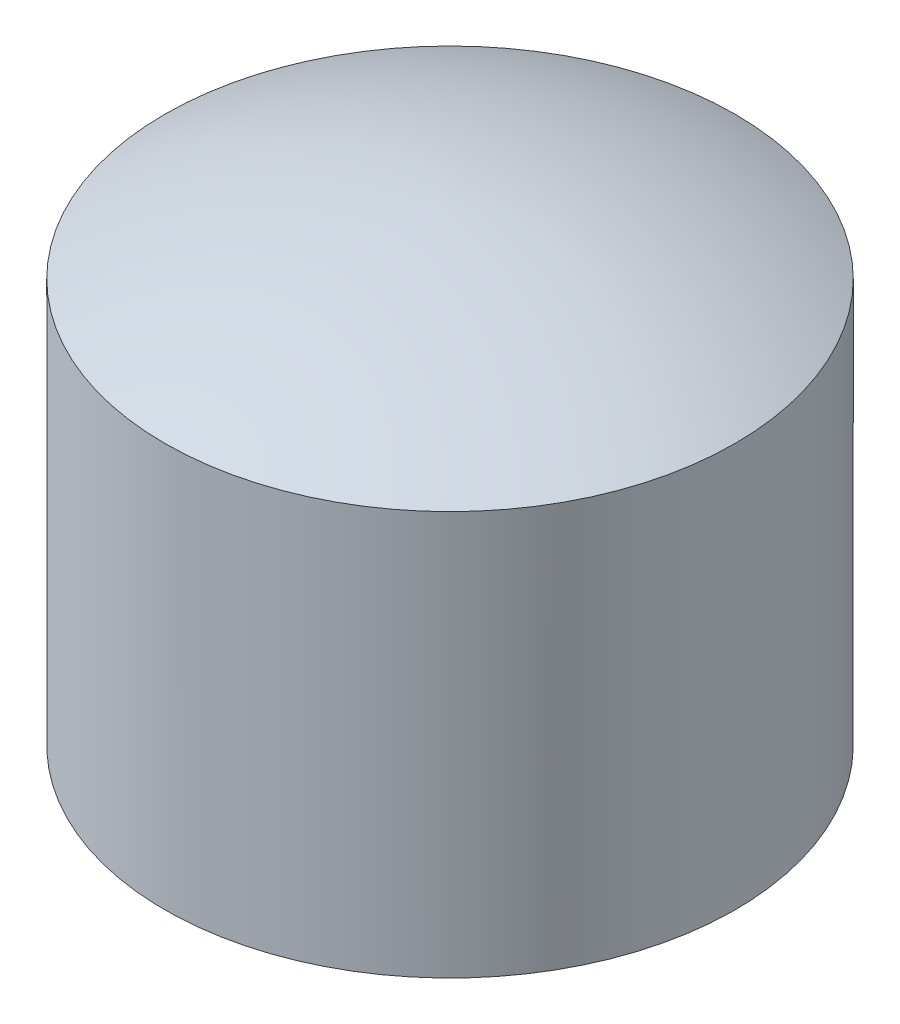
SolidWorks part; units mm, degrees
ref_plane "Ön Düzlem" through (0, 0, 0) normal (0, 0, 1) x (1, 0, 0)
ref_plane "Üst Düzlem" through (0, 0, 0) normal (0, 1, 0) x (1, 0, 0)
ref_plane "Sağ Düzlem" through (0, 0, 0) normal (1, 0, 0) x (0, 0, -1)
sketch "Çizim1" plane through (0, 0, 0) normal (0, 1, 0) x (1, 0, 0)
  circle A0 centre (0, 0) radius 4
  circle A1 centre (0, 0) radius 6
  dimension "D1" = 8
  dimension "D2" = 12
extrude "Yükseklik-Ekstrüzyon1" add sketch "Çizim1" along normal blind 4.5
sketch "Çizim2" plane through (0, 0, 0) normal (1, 0, 0) x (0, 0, -1)
  line L0 (0, 4.5) -> (0, 6.0057)
  line L1 (6, 4.5) -> (-6, 4.5) construction
  line L2 (0, 4.5) -> (6, 4.5)
  arc A0 (6, 4.5) -> (0, 6.0057) centre (-0.3374, -8.0459) ccw
revolve "Döndür1" add sketch "Çizim2" angle 360 about L0
sketch "Sketch1" plane through (0, 0, 0) normal (0, -1, 0) x (1, 0, 0)
  circle A0 centre (0, 0) radius 4
  circle A1 centre (0, 0) radius 6
extrude "Boss-Extrude1" add sketch "Sketch1" along normal blind 4
